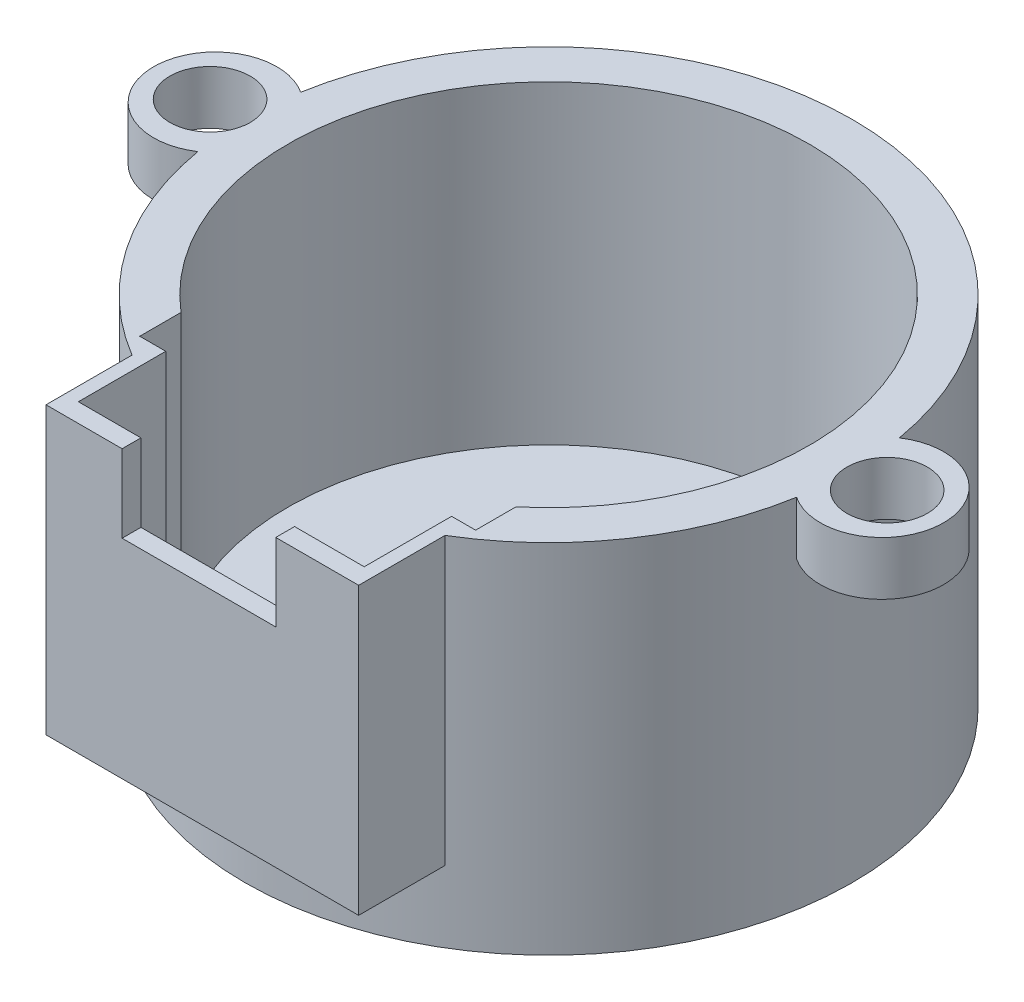
SolidWorks part; units mm, degrees
ref_plane "Front Plane" through (0, 0, 0) normal (0, 0, 1) x (1, 0, 0)
ref_plane "Top Plane" through (0, 0, 0) normal (0, 1, 0) x (1, 0, 0)
ref_plane "Right Plane" through (0, 0, 0) normal (1, 0, 0) x (0, 0, -1)
sketch "Sketch1" plane through (0, 0, 0) normal (0, 1, 0) x (1, 0, 0)
  circle A0 centre (0, 0) radius 17
  dimension "D1" = 34
extrude "Boss-Extrude1" add sketch "Sketch1" along normal blind 20
shell "Shell1" thickness 2.4
sketch "Sketch2" plane through (0, 20, 0) normal (0, 1, 0) x (1, 0, 0)
  line L0 (-14.6, 0) -> (37.717, 0) construction
  line L1 (0, 0) -> (0, -36.0151) construction
  circle A0 centre (0, 0) radius 14.6 construction
  circle A3 centre (18.6594, 0) radius 3.45
  circle A4 centre (-18.6594, 0) radius 3.45
extrude "Boss-Extrude3" add sketch "Sketch2" against normal blind 3
sketch "Sketch4" plane through (0, 20, 0) normal (0, 1, 0) x (1, 0, 0)
  line L0 (0, 0) -> (0, -29.7272) construction
  circle A0 centre (18.95, 0) radius 2.25
  circle A1 centre (-18.95, 0) radius 2.25
  dimension "D1" = 4.5
  dimension "D2" = 37.9
extrude "Cut-Extrude1" cut sketch "Sketch4" against normal blind 3
sketch "Sketch5" plane through (0, 20, 0) normal (0, 1, 0) x (1, 0, 0)
  line L1 (-8.7324, -11.7006) -> (8.7676, -11.7006)
  line L2 (-8.7324, -11.7006) -> (-8.7324, -19.4006)
  line L3 (-8.7324, -19.4006) -> (8.7676, -19.4006)
  line L4 (8.7676, -11.7006) -> (8.7676, -19.4006)
  circle A0 centre (0, 0) radius 14.6 construction
  dimension "D1" = 17.5
  dimension "D2" = 7.7
extrude "Boss-Extrude4" add sketch "Sketch5" against normal blind 16
sketch "Sketch6" plane through (0, 20, 0) normal (0, 1, 0) x (1, 0, 0)
  line L1 (-7.974, -18.3476) -> (8.026, -18.3476)
  line L2 (-7.974, -18.3476) -> (-7.974, -9.7476)
  line L3 (-7.974, -9.7476) -> (8.026, -9.7476)
  line L4 (8.026, -18.3476) -> (8.026, -9.7476)
  dimension "D1" = 16
  dimension "D2" = 8.6
extrude "Cut-Extrude2" cut sketch "Sketch6" against normal blind 14
sketch "Sketch7" plane through (0, 0, 19.4006) normal (0, 0, 1) x (1, 0, 0)
  line L1 (-4.4725, 15.661) -> (4.1275, 15.661)
  line L2 (-4.4725, 15.661) -> (-4.4725, 21.461)
  line L3 (-4.4725, 21.461) -> (4.1275, 21.461)
  line L4 (4.1275, 15.661) -> (4.1275, 21.461)
  dimension "D1" = 8.6
  dimension "D2" = 5.8
extrude "Cut-Extrude3" cut sketch "Sketch7" against normal blind 5
fillet "Fillet4" radius 1 1 edges at (0, 4, 11.7006)
sketch "Sketch8" plane through (0, 20, 0) normal (0, 1, 0) x (1, 0, 0)
  line L1 (-9.4317, -13.4558) -> (9.3683, -13.4558)
  line L2 (-9.4317, -13.4558) -> (-9.4317, -10.4558)
  line L3 (-9.4317, -10.4558) -> (9.3683, -10.4558)
  line L4 (9.3683, -13.4558) -> (9.3683, -10.4558)
  dimension "D1" = 18.8
  dimension "D2" = 3
extrude "Cut-Extrude4" cut sketch "Sketch8" against normal blind 16
